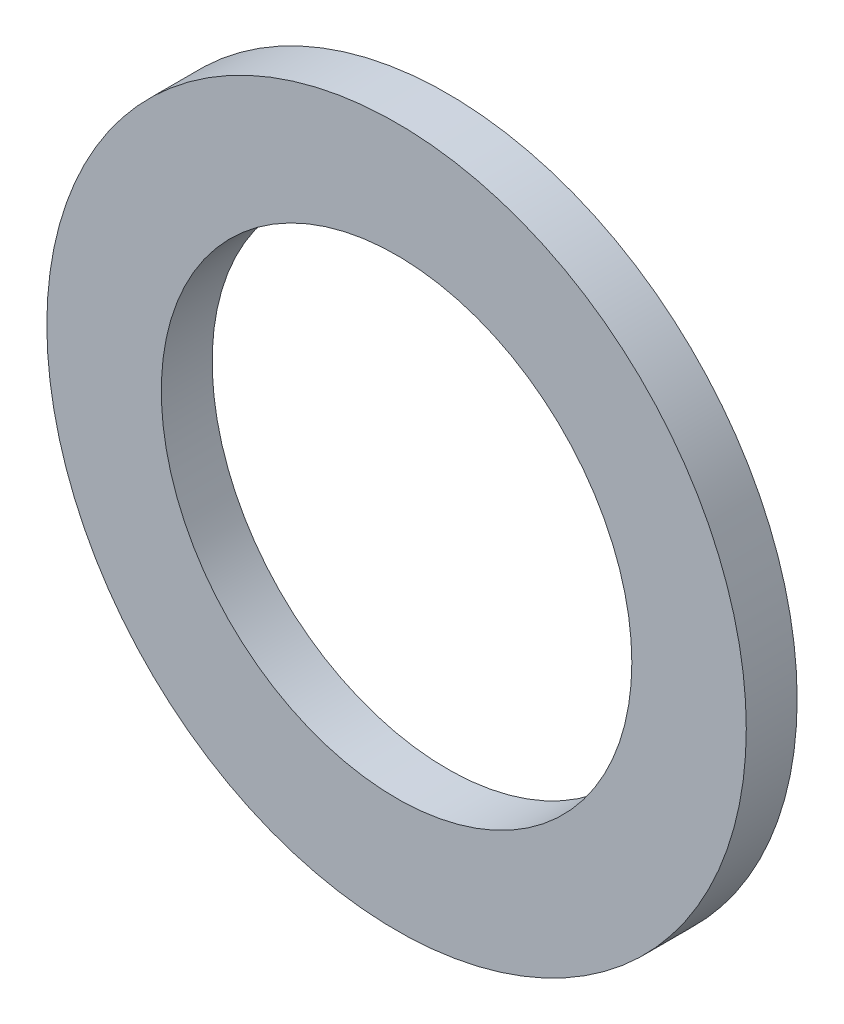
SolidWorks part; units mm, degrees
material "1.8159 (51CrV4)"
ref_plane "Front Plane" through (0, 0, 0) normal (0, 0, 1) x (1, 0, 0)
ref_plane "Top Plane" through (0, 0, 0) normal (0, 1, 0) x (1, 0, 0)
ref_plane "Right Plane" through (0, 0, 0) normal (1, 0, 0) x (0, 0, -1)
sketch "Sketch1" plane through (0, 0, 0) normal (0, 0, 1) x (1, 0, 0)
  circle A0 centre (-6.0534, 8.8639) radius 5.5
  circle A1 centre (-6.0534, 8.8639) radius 3.7
  dimension "D1" = 11
  dimension "D2" = 7.4
  dimension "D3" = 6.0534
  dimension "D4" = 8.8639
extrude "Boss-Extrude1" add sketch "Sketch1" along normal blind 0.8
